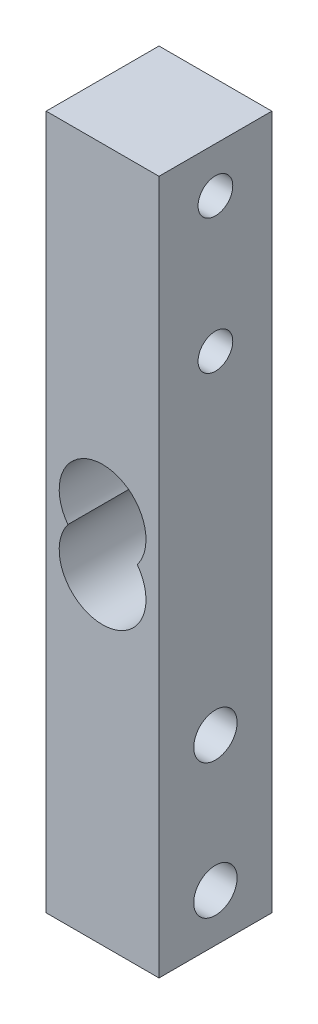
SolidWorks part; units mm, degrees
ref_plane "Front Plane" through (0, 0, 0) normal (0, 0, 1) x (1, 0, 0)
ref_plane "Top Plane" through (0, 0, 0) normal (0, 1, 0) x (1, 0, 0)
ref_plane "Right Plane" through (0, 0, 0) normal (1, 0, 0) x (0, 0, -1)
sketch "Sketch1" plane through (0, 0, 0) normal (0, 1, 0) x (1, 0, 0)
  line L1 (-6.5, 6.5) -> (6.5, 6.5)
  line L2 (-6.5, 6.5) -> (-6.5, -6.5)
  line L3 (-6.5, -6.5) -> (6.5, -6.5)
  line L4 (6.5, 6.5) -> (6.5, -6.5)
  line L5 (-6.5, 6.5) -> (6.5, -6.5) construction
  line L6 (-6.5, -6.5) -> (6.5, 6.5) construction
  point P0 (0, 0)
  dimension "D1" = 13
  dimension "D2" = 13
extrude "Boss-Extrude1" add sketch "Sketch1" along normal blind 80
sketch "Sketch2" plane through (0, 0, 6.5) normal (0, 0, 1) x (1, 0, 0)
  line L0 (0, 0) -> (0, 80) construction
  line L1 (-6.5, 0) -> (6.5, 0) construction
  line L2 (-6.5, 80) -> (6.5, 80) construction
  arc A0 (-4, 40) -> (4, 40) centre (0, 37) ccw
  arc A1 (4, 40) -> (-4, 40) centre (0, 43) ccw
  dimension "D1" = 32
  dimension "D2" = 32
  dimension "D3" = 10
  dimension "D4" = 10
extrude "Cut-Extrude1" cut sketch "Sketch2" against normal up to surface (13 mm away) up to face at (0, 40, -6.5)
sketch "Sketch3" plane through (6.5, 0, 0) normal (1, 0, 0) x (0, 0, -1)
  line L0 (0, 80) -> (0, 0) construction
  line L1 (-6.5, 80) -> (6.5, 80) construction
  line L2 (-6.5, 0) -> (6.5, 0) construction
  circle A0 centre (0, 74.8) radius 2
  circle A1 centre (0, 59.3) radius 2
  circle A2 centre (0, 21) radius 2.5
  circle A3 centre (0, 5.5) radius 2.5
  point P14 (0, 0)
  point P15 (0, 0)
  dimension "D1" = 3.2
  dimension "D2" = 4
  dimension "D3" = 11.5
  dimension "D4" = 10.5
  dimension "D5" = 3
  dimension "D6" = 5
extrude "Cut-Extrude2" cut sketch "Sketch3" against normal up to surface (13 mm away) up to face at (-6.5, 40, 0)
